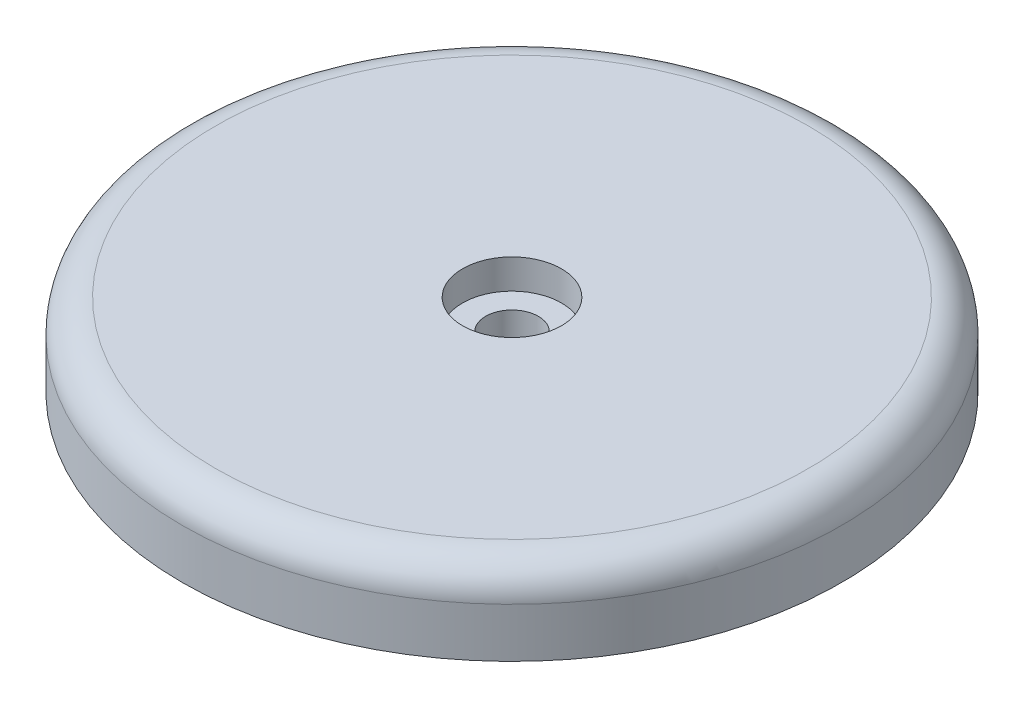
SolidWorks part; units mm, degrees
ref_plane "前视基准面" through (0, 0, 0) normal (0, 0, 1) x (1, 0, 0)
ref_plane "上视基准面" through (0, 0, 0) normal (0, 1, 0) x (1, 0, 0)
ref_plane "右视基准面" through (0, 0, 0) normal (1, 0, 0) x (0, 0, -1)
other "Configuration Table"
sketch "草图1" plane through (0, 0, 0) normal (0, 1, 0) x (1, 0, 0)
  circle A0 centre (0, 0) radius 20
  dimension "D1" = 40
extrude "凸台-拉伸1" add sketch "草图1" along normal blind 5
fillet "圆角1" radius 2 1 edges at (0, 5, 20)
sketch "草图2" plane through (0, 5, 0) normal (0, 1, 0) x (1, 0, 0)
  circle A0 centre (0, 0) radius 3
  dimension "D1" = 6
extrude "切除-拉伸1" cut sketch "草图2" against normal blind 1.8
sketch "草图3" plane through (0, 3.2, 0) normal (0, 1, 0) x (1, 0, 0)
  circle A0 centre (0, 0) radius 1.6
  dimension "D1" = 3.2
extrude "切除-拉伸2" cut sketch "草图3" against normal through all
